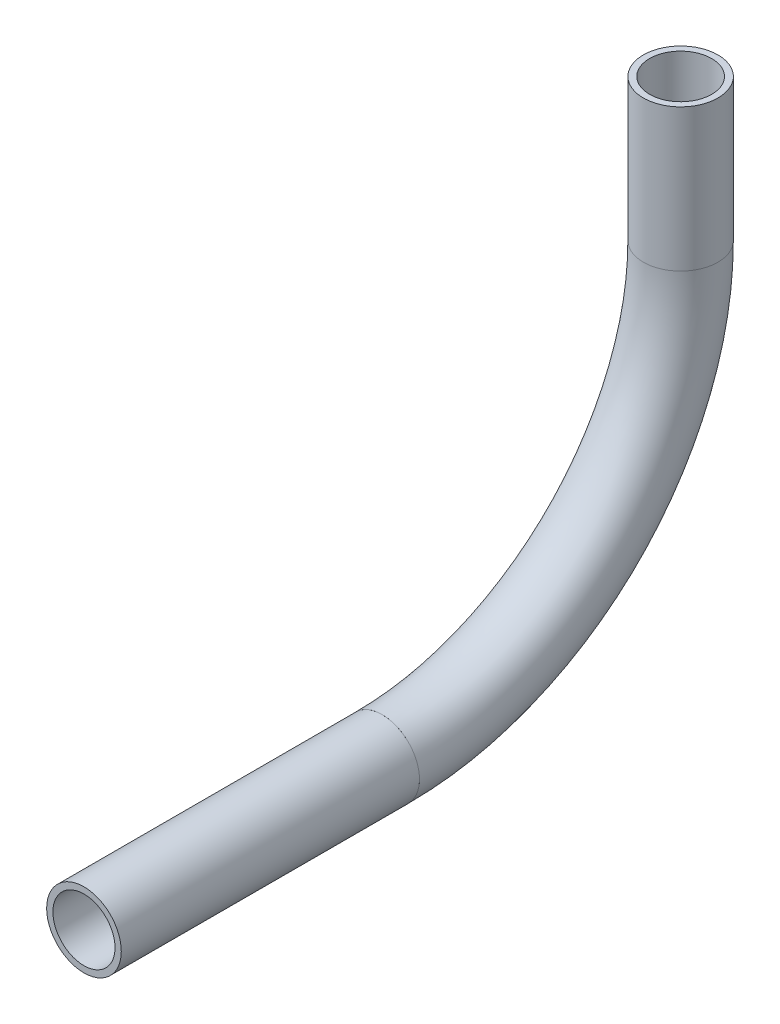
SolidWorks part; units mm, degrees
ref_plane "Front Plane" through (0, 0, 0) normal (0, 0, 1) x (1, 0, 0)
ref_plane "Top Plane" through (0, 0, 0) normal (0, 1, 0) x (1, 0, 0)
ref_plane "Right Plane" through (0, 0, 0) normal (1, 0, 0) x (0, 0, -1)
sketch "Sketch3" plane through (0, 0, 0) normal (1, 0, 0) x (0, 0, -1)
  line L0 (-259.1796, -201.5737) -> (-259.1796, -225.7805)
  line L1 (-309.9796, -276.5805) -> (-360.7276, -276.5805)
  arc A0 (-259.1796, -225.7805) -> (-309.9796, -276.5805) centre (-309.9796, -225.7805) cw
  point P2 (-283.2454, -256.2414)
  point P6 (-284.0666, -225.9534)
  dimension "D1" = 50.8
other "Pipe 0.5 SCH 40(1)"
ref_plane "Plane1" through (0, -201.5737, 259.1796) normal (0, -1, 0) x (0, 0, -1)
sketch "Sketch1" plane through (0, -201.5737, 259.1796) normal (0, -1, 0) x (0, 0, -1)
  circle A0 centre (0, 0) radius 6.35
  circle A1 centre (0, 0) radius 5.2832
  point P5 (0, 0)
  dimension "In_dia" = 12.7
  dimension "Out_dia" = 10.5664
